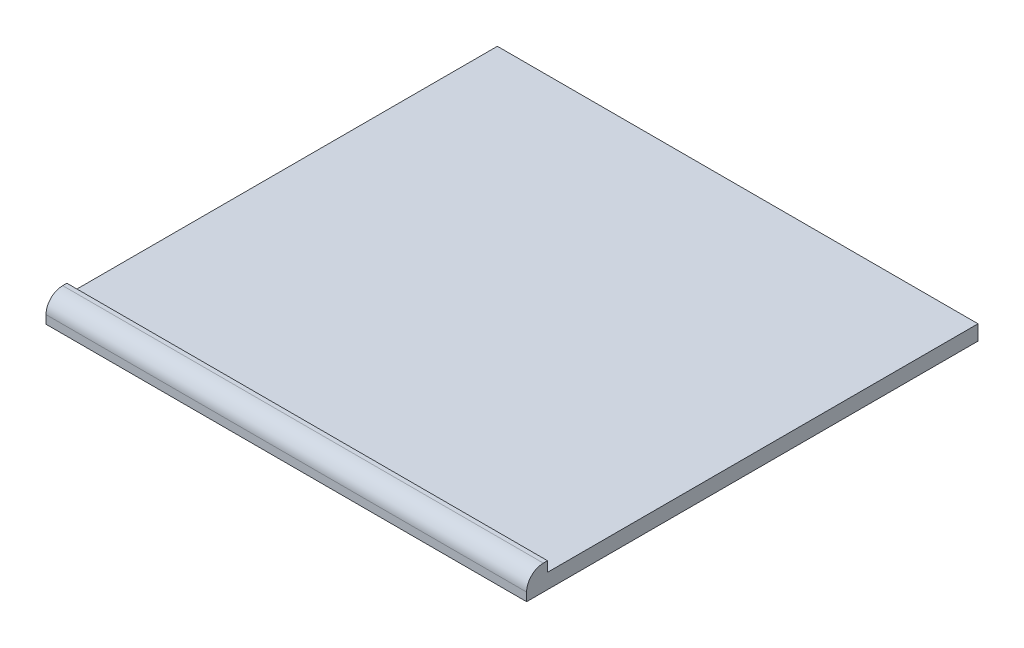
SolidWorks part; units mm, degrees
ref_plane "Front Plane" through (0, 0, 0) normal (0, 0, 1) x (1, 0, 0)
ref_plane "Top Plane" through (0, 0, 0) normal (0, 1, 0) x (1, 0, 0)
ref_plane "Right Plane" through (0, 0, 0) normal (1, 0, 0) x (0, 0, -1)
sketch "Sketch2" plane through (0, 0, 0) normal (0, 1, 0) x (1, 0, 0)
  line L2 (0, 0) -> (57.5, 0)
  line L3 (0, 0) -> (0, 54)
  line L4 (0, 54) -> (57.5, 54)
  line L5 (57.5, 0) -> (57.5, 54)
  dimension "D1" = 54
  dimension "D2" = 57.5
extrude "Boss-Extrude1" add sketch "Sketch2" along normal blind 1.8
sketch "Sketch3" plane through (0, 1.8, 0) normal (0, 1, 0) x (1, 0, 0)
  line L1 (0, 0) -> (57.5, 0)
  line L2 (0, 0) -> (0, 2.5)
  line L3 (0, 2.5) -> (57.5, 2.5)
  line L4 (57.5, 0) -> (57.5, 2.5)
  dimension "D1" = 2.5
extrude "Boss-Extrude2" add sketch "Sketch3" along normal blind 1.2
fillet "Fillet1" radius 2 1 edges at (28.75, 3, 0)
